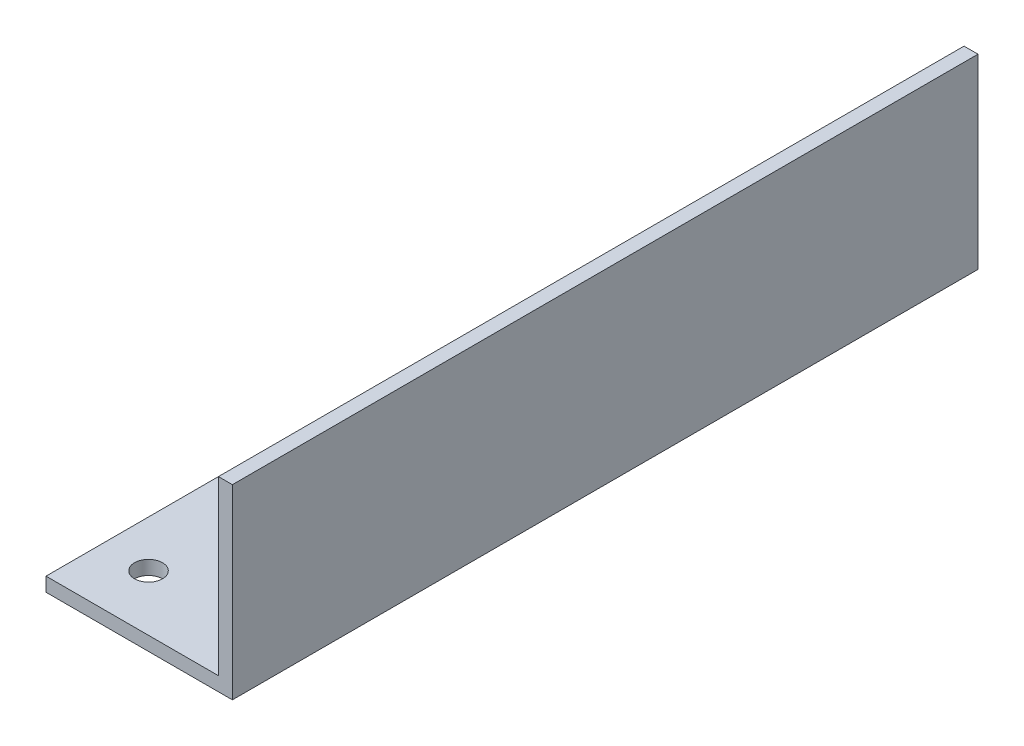
SolidWorks part; units mm, degrees
ref_plane "Plan de face" through (0, 0, 0) normal (0, 0, 1) x (1, 0, 0)
ref_plane "Plan de dessus" through (0, 0, 0) normal (0, 1, 0) x (1, 0, 0)
ref_plane "Plan de droite" through (0, 0, 0) normal (1, 0, 0) x (0, 0, -1)
sketch "Esquisse1" plane through (0, 0, 0) normal (0, 0, 1) x (1, 0, 0)
  line L0 (-29.2868, 12.1298) -> (-29.2868, 10.6298)
  line L1 (-29.2868, 10.6298) -> (-9.2868, 10.6298)
  line L2 (-9.2868, 10.6298) -> (-9.2868, 30.6298)
  line L3 (-9.2868, 30.6298) -> (-10.7868, 30.6298)
  line L4 (-10.7868, 30.6298) -> (-10.7868, 12.1298)
  line L5 (-10.7868, 12.1298) -> (-29.2868, 12.1298)
  dimension "D1" = 1.5
  dimension "D2" = 20
  dimension "D3" = 1.5
  dimension "D6" = 20
extrude "Extrusion1" add sketch "Esquisse1" along normal blind 80
sketch "Esquisse2" plane through (0, 10.6298, 0) normal (0, -1, 0) x (1, 0, 0)
  line L1 (-14.2868, 74) -> (-24.2868, 74) construction
  line L2 (-29.2868, 80) -> (-9.2868, 80) construction
  line L3 (-29.2868, 0) -> (-9.2868, 0) construction
  line L6 (-9.2868, 80) -> (-9.2868, 0) construction
  circle A0 centre (-14.2868, 74) radius 1.5
  circle A1 centre (-24.2868, 74) radius 1.5
  circle A2 centre (-14.2868, 16) radius 1.5
  circle A3 centre (-24.2868, 10) radius 1.5
  circle A4 centre (-19.2868, 40) radius 1.5
  point P16 (-9.2868, 40)
  dimension "D1" = 10
  dimension "D4" = 6
  dimension "D6" = 10
  dimension "D2" = 5
  dimension "D3" = 6
  dimension "D5" = 10
  dimension "D7" = 40
extrude "Extrusion2" cut sketch "Esquisse2" against normal blind 80
